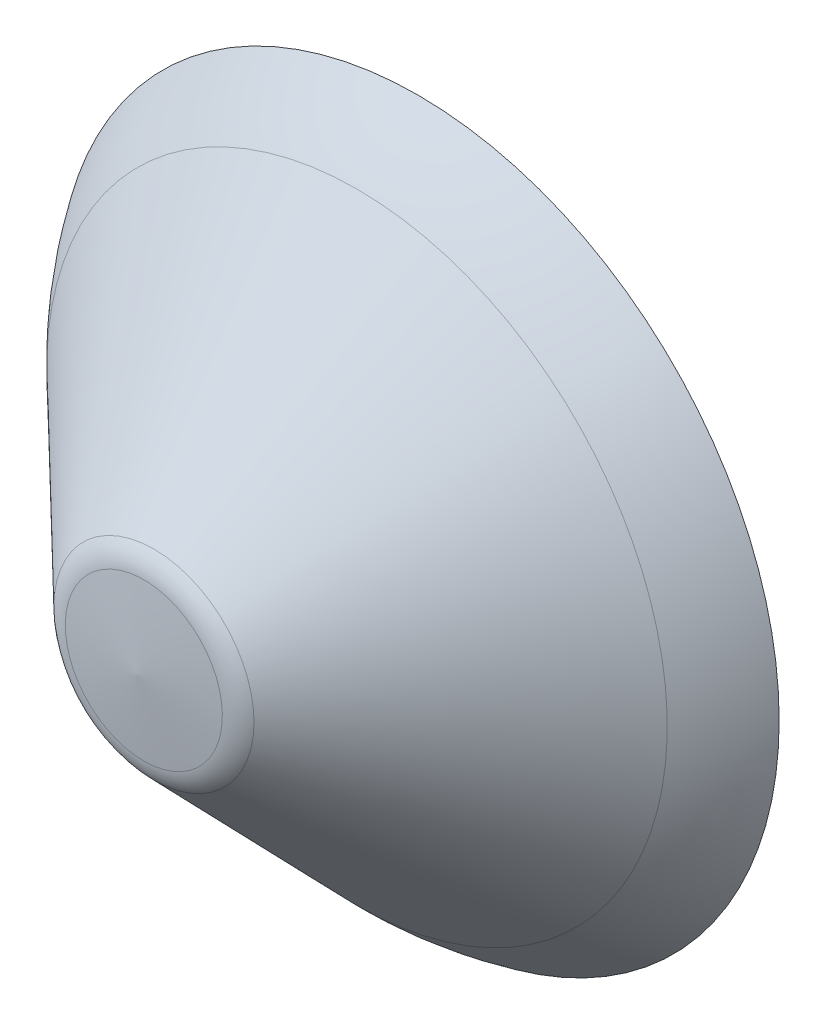
SolidWorks part; units mm, degrees
ref_plane "Front Plane" through (0, 0, 0) normal (0, 0, 1) x (1, 0, 0)
ref_plane "Top Plane" through (0, 0, 0) normal (0, 1, 0) x (1, 0, 0)
ref_plane "Right Plane" through (0, 0, 0) normal (1, 0, 0) x (0, 0, -1)
sketch "Sketch1" plane through (0, 0, 0) normal (1, 0, 0) x (0, 0, -1)
  line L0 (38.6899, 49.272) -> (38.6899, 0)
  line L8 (2.6219, 13.6591) -> (30.3375, 42.3467)
  line L10 (38.6899, 0) -> (0.2926, 0)
  line L12 (0.2926, 0) -> (100, 0) construction
  arc A7 (1.2463, 10.7174) -> (0.2926, 0) centre (299.5406, -21.2276) ccw
  arc A8 (30.3375, 42.3467) -> (38.6899, 49.272) centre (65.7574, 8.1269) cw
  arc A13 (2.6219, 13.6591) -> (1.2463, 10.7174) centre (6.2179, 10.185) ccw
  point P35 (96.5756, 47.5)
  dimension "D21" = 5
revolve "Revolve1" add sketch "Sketch1" angle 360 about L12
